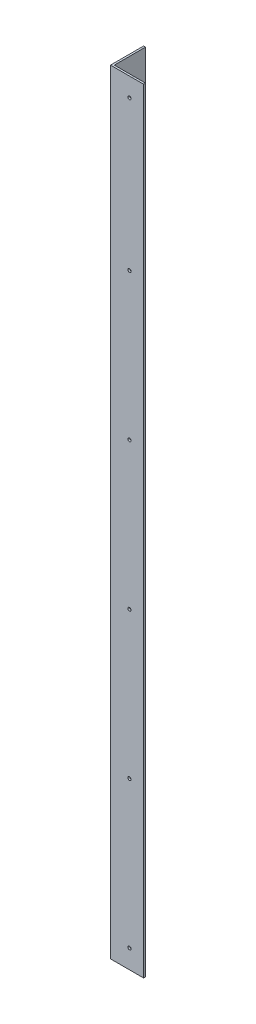
SolidWorks part; units mm, degrees
material "6063-O"
ref_plane "Piano frontale" through (0, 0, 0) normal (0, 0, 1) x (1, 0, 0)
ref_plane "Piano superiore" through (0, 0, 0) normal (0, 1, 0) x (1, 0, 0)
ref_plane "Piano destro" through (0, 0, 0) normal (1, 0, 0) x (0, 0, -1)
sketch "Schizzo2" plane through (0, 0, 0) normal (0, 1, 0) x (1, 0, 0)
  line L0 (0, 0) -> (35, 0)
  line L1 (35, 0) -> (35, 2)
  line L2 (35, 2) -> (2, 2)
  line L3 (2, 2) -> (2, 35)
  line L4 (2, 35) -> (0, 35)
  line L5 (0, 35) -> (0, 0)
  dimension "D1" = 35
  dimension "D2" = 35
  dimension "D3" = 2
  dimension "D4" = 2
extrude "Estrusione-Estrusione1" add sketch "Schizzo2" along normal blind 819
sketch "Schizzo3" plane through (0, 0, 0) normal (0, 0, 1) x (1, 0, 0)
  line L0 (20, 843.1808) -> (20, -52.7752) construction
  line L1 (0, 819) -> (0, 0) construction
  line L2 (0, 0) -> (35, 0) construction
  circle A0 centre (20, 20) radius 1.7
  circle A1 centre (20, 330.4) radius 1.7
  circle A2 centre (20, 485.6) radius 1.7
  circle A3 centre (20, 175.2) radius 1.7
  circle A4 centre (20, 640.8) radius 1.7
  circle A5 centre (20, 799) radius 1.7
  dimension "D4" = 330.4
  dimension "D8" = 3.4
  dimension "D1" = 20
  dimension "D2" = 20
  dimension "D3" = 175.2
  dimension "D5" = 485.6
  dimension "D6" = 640.8
  dimension "D7" = 799
extrude "Taglio-Estrusione1" cut sketch "Schizzo3" against normal through all
